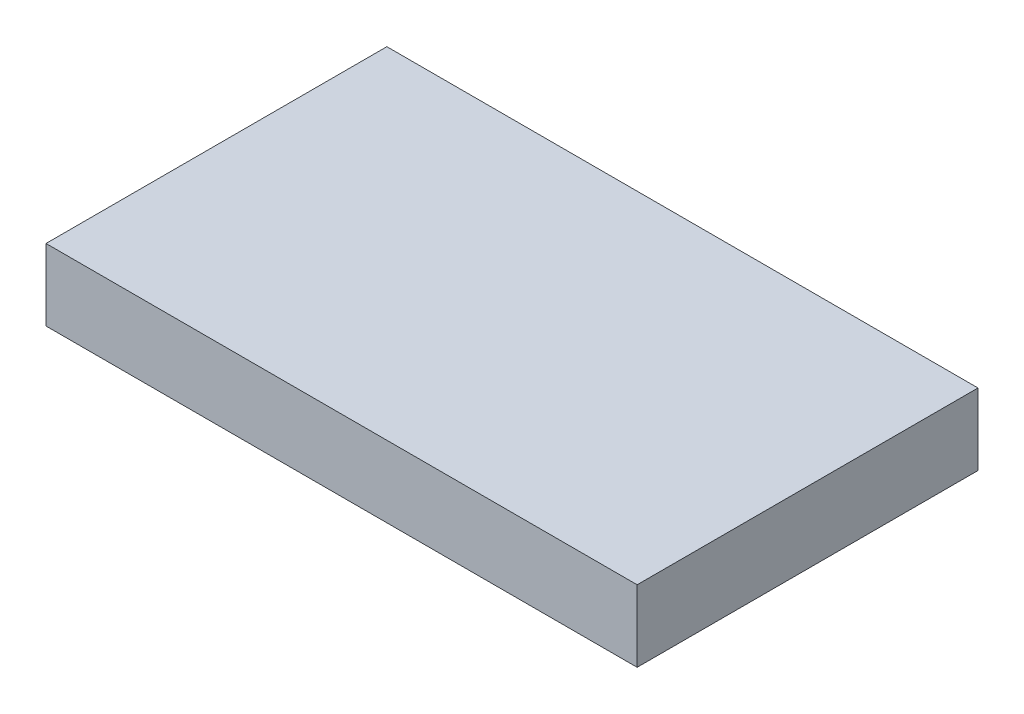
SolidWorks part; units mm, degrees
material "wifi"
ref_plane "Front Plane" through (0, 0, 0) normal (0, 0, 1) x (1, 0, 0)
ref_plane "Top Plane" through (0, 0, 0) normal (0, 1, 0) x (1, 0, 0)
ref_plane "Right Plane" through (0, 0, 0) normal (1, 0, 0) x (0, 0, -1)
sketch "Sketch1" plane through (0, 0, 0) normal (0, 1, 0) x (1, 0, 0)
  line L1 (-28.4954, 7.5437) -> (-3.6954, 7.5437)
  line L2 (-28.4954, 7.5437) -> (-28.4954, 21.8437)
  line L3 (-28.4954, 21.8437) -> (-3.6954, 21.8437)
  line L4 (-3.6954, 7.5437) -> (-3.6954, 21.8437)
  dimension "D1" = 24.8
  dimension "D2" = 14.3
extrude "Boss-Extrude1" add sketch "Sketch1" along normal blind 3
